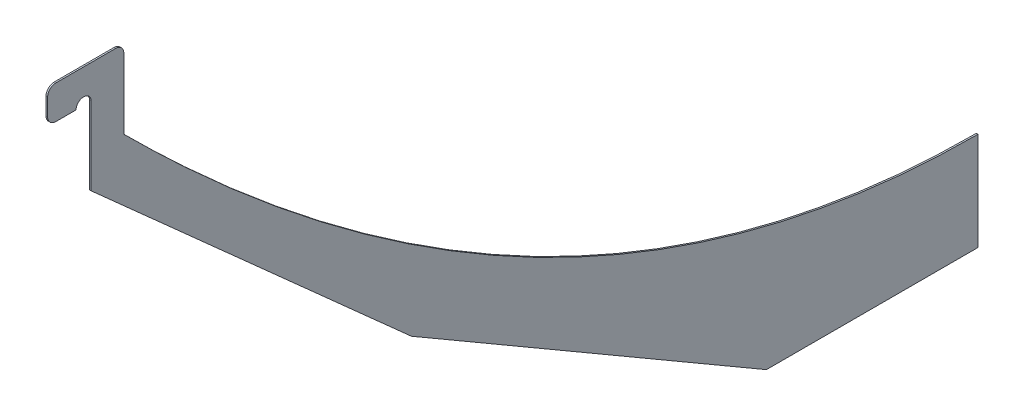
SolidWorks part; units mm, degrees
other "DetailItem1"
material "6061 Alloy"
ref_plane "Front Plane" through (0, 0, 0) normal (0, 0, 1) x (1, 0, 0)
ref_plane "Top Plane" through (0, 0, 0) normal (0, 1, 0) x (1, 0, 0)
ref_plane "Right Plane" through (0, 0, 0) normal (1, 0, 0) x (0, 0, -1)
sketch "Sketch1" plane through (0, 0, 0) normal (1, 0, 0) x (0, 0, -1)
  line L0 (-328.7708, -230.9239) -> (0, -230.9239)
  line L1 (0, -230.9239) -> (0, -78.5239)
  line L2 (-1327.1499, 694.2527) -> (-1327.1502, 585.0511)
  line L3 (-1377.9499, 654.9011) -> (-1377.9499, 534.2511)
  line L10 (-1377.9499, 534.2511) -> (-880.3817, 89.8627)
  line L12 (-328.7708, -230.9239) -> (-880.3817, 89.8627)
  line L19 (-1432.8727, 654.9011) -> (-1401.3687, 654.9011)
  line L20 (-1445.5727, 694.2527) -> (-1445.5727, 667.6011)
  line L21 (-1339.8499, 706.9527) -> (-1432.8727, 706.9527)
  arc A4 (-1377.9499, 654.9011) -> (-1401.3687, 654.9011) centre (-1389.6593, 654.9011) ccw
  arc A5 (-1445.5727, 667.6011) -> (-1432.8727, 654.9011) centre (-1432.8727, 667.6011) ccw
  arc A6 (-1432.8727, 706.9527) -> (-1445.5727, 694.2527) centre (-1432.8727, 694.2527) ccw
  arc A7 (-1327.1499, 694.2527) -> (-1339.8499, 706.9527) centre (-1339.8499, 694.2527) ccw
  parabola Q1 (0, -78.5239) -> (-1327.1502, 585.0511) focus (0, 585.0511) apex (0, -78.5239)
  dimension "D1" = 11.7094
extrude "Boss-Extrude3" add sketch "Sketch1" along normal blind 2.54
